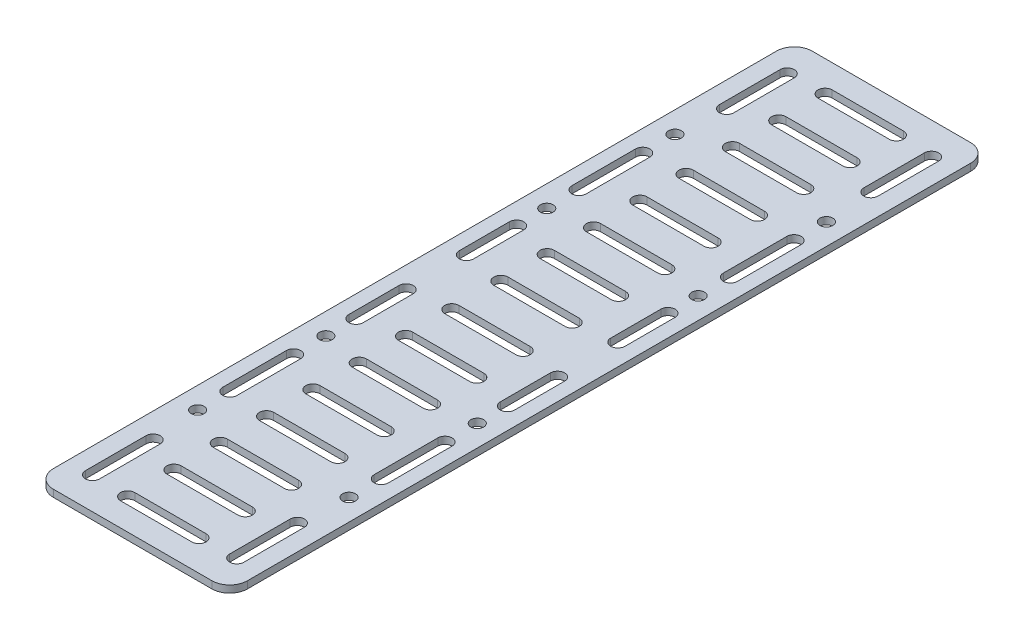
SolidWorks part; units mm, degrees
ref_plane "Front Plane" through (0, 0, 0) normal (0, 0, 1) x (1, 0, 0)
ref_plane "Top Plane" through (0, 0, 0) normal (0, 1, 0) x (1, 0, 0)
ref_plane "Right Plane" through (0, 0, 0) normal (1, 0, 0) x (0, 0, -1)
sketch "Sketch1" plane through (0, 0, 0) normal (0, 1, 0) x (1, 0, 0)
  line L1 (-27.25, 106.5) -> (27.25, 106.5)
  line L2 (-27.25, 106.5) -> (-27.25, -106.5)
  line L3 (-27.25, -106.5) -> (27.25, -106.5)
  line L4 (27.25, 106.5) -> (27.25, -106.5)
  line L5 (-27.25, 106.5) -> (27.25, -106.5) construction
  line L6 (-27.25, -106.5) -> (27.25, 106.5) construction
  point P0 (0, 0)
  dimension "D1" = 54.5
  dimension "D2" = 213
extrude "Boss-Extrude1" add sketch "Sketch1" along normal blind 2
hole_wizard "M3 Clearance Hole1" positions "Sketch3" profile "Sketch4" hole size "M3" standard "ANSI Metric" end condition through all
sketch "Sketch3" plane through (0, 2, 0) normal (0, 1, 0) x (1, 0, 0)
  line L0 (0, 0) -> (0, 100.7242) construction
  line L2 (0, 0) -> (-58.9219, 0) construction
  line L4 (-27.25, 106.5) -> (-27.25, -106.5) construction
  point P0 (-21.25, 67)
  point P15 (-21.25, 31)
  point P17 (21.25, 67)
  point P18 (21.25, 31)
  point P20 (21.25, -31)
  point P21 (21.25, -67)
  point P22 (-21.25, -67)
  point P23 (-21.25, -31)
  dimension "D1" = 6
  dimension "D2" = 31
  dimension "D3" = 36
sketch "Sketch4" plane through (-21.25, 2, -67) normal (1, 0, 0) x (0, 0, 1)
  line L0 (0, 0) -> (0, 2)
  line L1 (0, 2) -> (1.8, 2)
  line L2 (1.8, 2) -> (1.8, 0)
  line L5 (1.8, 0) -> (0, 0)
  line L11 (0, -6.35) -> (0, 107.95) construction
  dimension "Thru Hole Dia." = 3.6
  dimension "Thru Hole Depth" = 2
sketch "Sketch5" plane through (0, 2, 0) normal (0, 1, 0) x (1, 0, 0)
  line L0 (-20.25, 97.5) -> (-20.25, 80.5) construction
  line L1 (-18.25, 97.5) -> (-18.25, 80.5)
  line L2 (-22.25, 97.5) -> (-22.25, 80.5)
  line L3 (0, 0) -> (0, 101.9957) construction
  line L4 (20.25, 97.5) -> (20.25, 80.5) construction
  line L5 (18.25, 97.5) -> (18.25, 80.5)
  line L6 (22.25, 97.5) -> (22.25, 80.5)
  line L7 (27.25, 106.5) -> (-27.25, 106.5) construction
  line L8 (-10, 97.8852) -> (10, 97.8852) construction
  line L9 (-10, 99.8852) -> (10, 99.8852)
  line L10 (-10, 95.8852) -> (10, 95.8852)
  line L11 (-10, 84.8852) -> (10, 84.8852) construction
  line L12 (-10, 86.8852) -> (10, 86.8852)
  line L13 (-10, 82.8852) -> (10, 82.8852)
  line L14 (-10, 71.8852) -> (10, 71.8852) construction
  line L15 (-10, 73.8852) -> (10, 73.8852)
  line L16 (-10, 69.8852) -> (10, 69.8852)
  line L17 (-10, 58.8852) -> (10, 58.8852) construction
  line L18 (-10, 60.8852) -> (10, 60.8852)
  line L19 (-10, 56.8852) -> (10, 56.8852)
  line L20 (-10, 45.8852) -> (10, 45.8852) construction
  line L21 (-10, 47.8852) -> (10, 47.8852)
  line L22 (-10, 43.8852) -> (10, 43.8852)
  line L23 (-10, 32.8852) -> (10, 32.8852) construction
  line L24 (-10, 34.8852) -> (10, 34.8852)
  line L25 (-10, 30.8852) -> (10, 30.8852)
  line L26 (-10, 19.8852) -> (10, 19.8852) construction
  line L27 (-10, 21.8852) -> (10, 21.8852)
  line L28 (-10, 17.8852) -> (10, 17.8852)
  line L29 (-10, 6.8852) -> (10, 6.8852) construction
  line L30 (-10, 8.8852) -> (10, 8.8852)
  line L31 (-10, 4.8852) -> (10, 4.8852)
  line L32 (-21.25, 67) -> (-21.25, 31) construction
  line L33 (-21.25, 57.9327) -> (-21.25, 40.0673) construction
  line L34 (-19.25, 57.9327) -> (-19.25, 40.0673)
  line L35 (-23.25, 57.9327) -> (-23.25, 40.0673)
  line L36 (-21.25, 31) -> (-21.25, 0) construction
  line L37 (-21.25, 22.5337) -> (-21.25, 8.4663) construction
  line L38 (-19.25, 22.5337) -> (-19.25, 8.4663)
  line L39 (-23.25, 22.5337) -> (-23.25, 8.4663)
  line L40 (21.25, 57.9327) -> (21.25, 40.0673) construction
  line L41 (19.25, 57.9327) -> (19.25, 40.0673)
  line L42 (23.25, 57.9327) -> (23.25, 40.0673)
  line L43 (21.25, 22.5337) -> (21.25, 8.4663) construction
  line L44 (19.25, 22.5337) -> (19.25, 8.4663)
  line L45 (23.25, 22.5337) -> (23.25, 8.4663)
  line L46 (0, 0) -> (46.6314, 0) construction
  line L47 (-20.25, -97.5) -> (-20.25, -80.5) construction
  line L48 (-18.25, -97.5) -> (-18.25, -80.5)
  line L49 (-22.25, -97.5) -> (-22.25, -80.5)
  line L50 (20.25, -97.5) -> (20.25, -80.5) construction
  line L51 (18.25, -97.5) -> (18.25, -80.5)
  line L52 (22.25, -97.5) -> (22.25, -80.5)
  line L53 (-10, -97.8852) -> (10, -97.8852) construction
  line L54 (-10, -99.8852) -> (10, -99.8852)
  line L55 (-10, -95.8852) -> (10, -95.8852)
  line L56 (-10, -84.8852) -> (10, -84.8852) construction
  line L57 (-10, -86.8852) -> (10, -86.8852)
  line L58 (-10, -82.8852) -> (10, -82.8852)
  line L59 (-10, -71.8852) -> (10, -71.8852) construction
  line L60 (-10, -73.8852) -> (10, -73.8852)
  line L61 (-10, -69.8852) -> (10, -69.8852)
  line L62 (-10, -58.8852) -> (10, -58.8852) construction
  line L63 (-10, -60.8852) -> (10, -60.8852)
  line L64 (-10, -56.8852) -> (10, -56.8852)
  line L65 (-10, -45.8852) -> (10, -45.8852) construction
  line L66 (-10, -47.8852) -> (10, -47.8852)
  line L67 (-10, -43.8852) -> (10, -43.8852)
  line L68 (-10, -32.8852) -> (10, -32.8852) construction
  line L69 (-10, -34.8852) -> (10, -34.8852)
  line L70 (-10, -30.8852) -> (10, -30.8852)
  line L71 (-10, -19.8852) -> (10, -19.8852) construction
  line L72 (-10, -21.8852) -> (10, -21.8852)
  line L73 (-10, -17.8852) -> (10, -17.8852)
  line L74 (-10, -6.8852) -> (10, -6.8852) construction
  line L75 (-10, -8.8852) -> (10, -8.8852)
  line L76 (-10, -4.8852) -> (10, -4.8852)
  line L77 (-21.25, -57.9327) -> (-21.25, -40.0673) construction
  line L78 (-19.25, -57.9327) -> (-19.25, -40.0673)
  line L79 (-23.25, -57.9327) -> (-23.25, -40.0673)
  line L80 (-21.25, -22.5337) -> (-21.25, -8.4663) construction
  line L81 (-19.25, -22.5337) -> (-19.25, -8.4663)
  line L82 (-23.25, -22.5337) -> (-23.25, -8.4663)
  line L83 (21.25, -57.9327) -> (21.25, -40.0673) construction
  line L84 (19.25, -57.9327) -> (19.25, -40.0673)
  line L85 (23.25, -57.9327) -> (23.25, -40.0673)
  line L86 (21.25, -22.5337) -> (21.25, -8.4663) construction
  line L87 (19.25, -22.5337) -> (19.25, -8.4663)
  line L88 (23.25, -22.5337) -> (23.25, -8.4663)
  arc A0 (-18.25, 97.5) -> (-22.25, 97.5) centre (-20.25, 97.5) ccw
  arc A1 (-22.25, 80.5) -> (-18.25, 80.5) centre (-20.25, 80.5) ccw
  arc A2 (18.25, 97.5) -> (22.25, 97.5) centre (20.25, 97.5) cw
  arc A3 (22.25, 80.5) -> (18.25, 80.5) centre (20.25, 80.5) cw
  arc A4 (-10, 99.8852) -> (-10, 95.8852) centre (-10, 97.8852) ccw
  arc A5 (10, 95.8852) -> (10, 99.8852) centre (10, 97.8852) ccw
  arc A6 (-10, 86.8852) -> (-10, 82.8852) centre (-10, 84.8852) ccw
  arc A7 (10, 82.8852) -> (10, 86.8852) centre (10, 84.8852) ccw
  arc A8 (-10, 73.8852) -> (-10, 69.8852) centre (-10, 71.8852) ccw
  arc A9 (10, 69.8852) -> (10, 73.8852) centre (10, 71.8852) ccw
  arc A10 (-10, 60.8852) -> (-10, 56.8852) centre (-10, 58.8852) ccw
  arc A11 (10, 56.8852) -> (10, 60.8852) centre (10, 58.8852) ccw
  arc A12 (-10, 47.8852) -> (-10, 43.8852) centre (-10, 45.8852) ccw
  arc A13 (10, 43.8852) -> (10, 47.8852) centre (10, 45.8852) ccw
  arc A14 (-10, 34.8852) -> (-10, 30.8852) centre (-10, 32.8852) ccw
  arc A15 (10, 30.8852) -> (10, 34.8852) centre (10, 32.8852) ccw
  arc A16 (-10, 21.8852) -> (-10, 17.8852) centre (-10, 19.8852) ccw
  arc A17 (10, 17.8852) -> (10, 21.8852) centre (10, 19.8852) ccw
  arc A18 (-10, 8.8852) -> (-10, 4.8852) centre (-10, 6.8852) ccw
  arc A19 (10, 4.8852) -> (10, 8.8852) centre (10, 6.8852) ccw
  arc A20 (-19.25, 57.9327) -> (-23.25, 57.9327) centre (-21.25, 57.9327) ccw
  arc A21 (-23.25, 40.0673) -> (-19.25, 40.0673) centre (-21.25, 40.0673) ccw
  arc A22 (-19.25, 22.5337) -> (-23.25, 22.5337) centre (-21.25, 22.5337) ccw
  arc A23 (-23.25, 8.4663) -> (-19.25, 8.4663) centre (-21.25, 8.4663) ccw
  arc A24 (19.25, 57.9327) -> (23.25, 57.9327) centre (21.25, 57.9327) cw
  arc A25 (23.25, 40.0673) -> (19.25, 40.0673) centre (21.25, 40.0673) cw
  arc A26 (19.25, 22.5337) -> (23.25, 22.5337) centre (21.25, 22.5337) cw
  arc A27 (23.25, 8.4663) -> (19.25, 8.4663) centre (21.25, 8.4663) cw
  arc A28 (-18.25, -97.5) -> (-22.25, -97.5) centre (-20.25, -97.5) cw
  arc A29 (-22.25, -80.5) -> (-18.25, -80.5) centre (-20.25, -80.5) cw
  arc A30 (18.25, -97.5) -> (22.25, -97.5) centre (20.25, -97.5) ccw
  arc A31 (22.25, -80.5) -> (18.25, -80.5) centre (20.25, -80.5) ccw
  arc A32 (-10, -99.8852) -> (-10, -95.8852) centre (-10, -97.8852) cw
  arc A33 (10, -95.8852) -> (10, -99.8852) centre (10, -97.8852) cw
  arc A34 (-10, -86.8852) -> (-10, -82.8852) centre (-10, -84.8852) cw
  arc A35 (10, -82.8852) -> (10, -86.8852) centre (10, -84.8852) cw
  arc A36 (-10, -73.8852) -> (-10, -69.8852) centre (-10, -71.8852) cw
  arc A37 (10, -69.8852) -> (10, -73.8852) centre (10, -71.8852) cw
  arc A38 (-10, -60.8852) -> (-10, -56.8852) centre (-10, -58.8852) cw
  arc A39 (10, -56.8852) -> (10, -60.8852) centre (10, -58.8852) cw
  arc A40 (-10, -47.8852) -> (-10, -43.8852) centre (-10, -45.8852) cw
  arc A41 (10, -43.8852) -> (10, -47.8852) centre (10, -45.8852) cw
  arc A42 (-10, -34.8852) -> (-10, -30.8852) centre (-10, -32.8852) cw
  arc A43 (10, -30.8852) -> (10, -34.8852) centre (10, -32.8852) cw
  arc A44 (-10, -21.8852) -> (-10, -17.8852) centre (-10, -19.8852) cw
  arc A45 (10, -17.8852) -> (10, -21.8852) centre (10, -19.8852) cw
  arc A46 (-10, -8.8852) -> (-10, -4.8852) centre (-10, -6.8852) cw
  arc A47 (10, -4.8852) -> (10, -8.8852) centre (10, -6.8852) cw
  arc A48 (-19.25, -57.9327) -> (-23.25, -57.9327) centre (-21.25, -57.9327) cw
  arc A49 (-23.25, -40.0673) -> (-19.25, -40.0673) centre (-21.25, -40.0673) cw
  arc A50 (-19.25, -22.5337) -> (-23.25, -22.5337) centre (-21.25, -22.5337) cw
  arc A51 (-23.25, -8.4663) -> (-19.25, -8.4663) centre (-21.25, -8.4663) cw
  arc A52 (19.25, -57.9327) -> (23.25, -57.9327) centre (21.25, -57.9327) ccw
  arc A53 (23.25, -40.0673) -> (19.25, -40.0673) centre (21.25, -40.0673) ccw
  arc A54 (19.25, -22.5337) -> (23.25, -22.5337) centre (21.25, -22.5337) ccw
  arc A55 (23.25, -8.4663) -> (19.25, -8.4663) centre (21.25, -8.4663) ccw
  point P2 (-20.25, 89)
  point P12 (20.25, 89)
  point P21 (0, 97.8852)
  point P29 (0, 84.8852)
  point P36 (0, 71.8852)
  point P43 (0, 58.8852)
  point P50 (0, 45.8852)
  point P57 (0, 32.8852)
  point P64 (0, 19.8852)
  point P71 (0, 6.8852)
  point P81 (-21.25, 49)
  point P89 (-21.25, 15.5)
  point P96 (21.25, 49)
  point P103 (21.25, 15.5)
  point P111 (-20.25, -89)
  point P118 (20.25, -89)
  point P125 (0, -97.8852)
  point P132 (0, -84.8852)
  point P139 (0, -71.8852)
  point P146 (0, -58.8852)
  point P153 (0, -45.8852)
  point P160 (0, -32.8852)
  point P167 (0, -19.8852)
  point P174 (0, -6.8852)
  point P181 (-21.25, -49)
  point P188 (-21.25, -15.5)
  point P195 (21.25, -49)
  point P202 (21.25, -15.5)
  dimension "D1" = 4
  dimension "D2" = 36.5
  dimension "D3" = 9
  dimension "D4" = 17
  dimension "D5" = 4
  dimension "D6" = 20
  dimension "D8" = 4
  dimension "D9" = 4
  dimension "D7" = 8
extrude "Cut-Extrude1" cut sketch "Sketch5" against normal through all
fillet "Fillet1" radius 5 4 edges at (-27.25, 1, -106.5) (27.25, 1, -106.5) (-27.25, 1, 106.5) (27.25, 1, 106.5)
